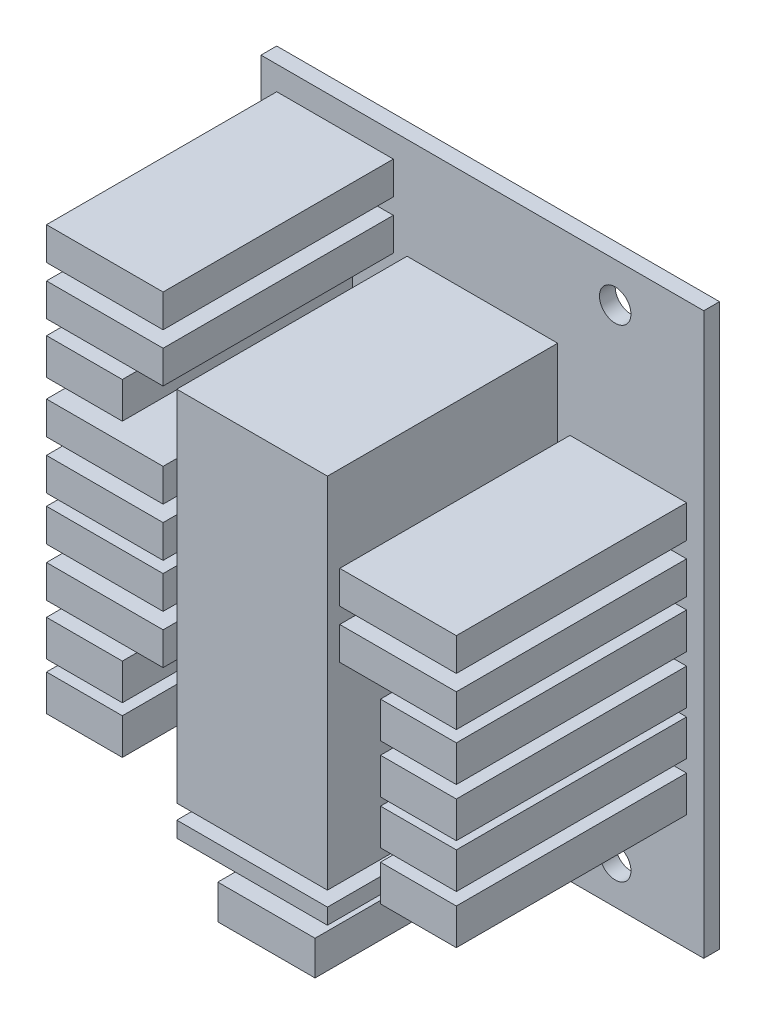
SolidWorks part; units mm, degrees
ref_plane "Plan de face" through (0, 0, 0) normal (0, 0, 1) x (1, 0, 0)
ref_plane "Plan de dessus" through (0, 0, 0) normal (0, 1, 0) x (1, 0, 0)
ref_plane "Plan de droite" through (0, 0, 0) normal (1, 0, 0) x (0, 0, -1)
sketch "Esquisse1" plane through (0, 0, 0) normal (0, 0, 1) x (1, 0, 0)
  line L0 (-22.5, -28.5) -> (22.5, -28.5)
  line L2 (22.5, -28.5) -> (22.5, 28.5)
  line L3 (22.5, 28.5) -> (-22.5, 28.5)
  line L4 (-22.5, -28.5) -> (-22.5, 28.5)
  line L5 (22.5, -28.5) -> (-22.5, 28.5) construction
  line L6 (22.5, 28.5) -> (-22.5, -28.5) construction
  circle A1 centre (13.5, 24.5) radius 1.6
  circle A2 centre (13.5, -24.5) radius 1.6
  circle A3 centre (-9.5, -24.5) radius 1.6
  point P0 (0, 0)
  dimension "D3" = 4
  dimension "D4" = 9
  dimension "D5" = 23
  dimension "D6" = 49
  dimension "D1" = 45
  dimension "D2" = 57
extrude "Boss.-Extru.1" add sketch "Esquisse1" along normal blind 1.6
sketch "Esquisse2" plane through (0, 0, 1.6) normal (0, 0, 1) x (1, 0, 0)
  line L0 (8.9033, 2.4603) -> (20.7535, 2.4603)
  line L1 (7.6551, -18.2198) -> (-7.6551, -18.2198)
  line L2 (7.6551, -18.2198) -> (7.6551, 18.2198)
  line L3 (7.6551, 18.2198) -> (-7.6551, 18.2198)
  line L4 (-7.6551, -18.2198) -> (-7.6551, 18.2198)
  line L5 (7.6551, -18.2198) -> (-7.6551, 18.2198) construction
  line L6 (7.6551, 18.2198) -> (-7.6551, -18.2198) construction
  line L7 (7.6551, -21.3078) -> (-7.6551, -21.3078)
  line L8 (7.6551, -21.3078) -> (7.6551, -19.71)
  line L9 (7.6551, -19.71) -> (-7.6551, -19.71)
  line L10 (-7.6551, -21.3078) -> (-7.6551, -19.71)
  line L11 (7.6551, -21.3078) -> (-7.6551, -19.71) construction
  line L12 (7.6551, -19.71) -> (-7.6551, -21.3078) construction
  line L13 (8.9033, 10.7312) -> (20.7535, 10.7312)
  line L14 (8.9033, 10.7312) -> (8.9033, 7.4015)
  line L15 (8.9033, 7.4015) -> (20.7535, 7.4015)
  line L16 (20.7535, 10.7312) -> (20.7535, 7.4015)
  line L17 (8.9033, 10.7312) -> (20.7535, 7.4015) construction
  line L18 (8.9033, 7.4015) -> (20.7535, 10.7312) construction
  line L20 (-3.4878, -26.5802) -> (6.3944, -26.5802)
  line L21 (-3.4878, -26.5802) -> (-3.4878, -23.0797)
  line L22 (-3.4878, -23.0797) -> (6.3944, -23.0797)
  line L23 (6.3944, -26.5802) -> (6.3944, -23.0797)
  line L24 (-3.4878, -26.5802) -> (6.3944, -23.0797) construction
  line L25 (20.7535, 5.7901) -> (20.7535, 2.4603)
  line L26 (8.9033, 5.7901) -> (20.7535, 2.4603) construction
  line L27 (8.9033, 5.7901) -> (20.7535, 5.7901)
  line L28 (8.9033, 5.7901) -> (8.9033, 2.4603)
  line L29 (8.9033, 2.4603) -> (20.7535, 5.7901) construction
  line L30 (13.0464, 1.2941) -> (13.0464, -2.3762)
  line L31 (13.0464, -2.3762) -> (20.7535, -2.3762)
  line L32 (20.7535, 1.2941) -> (20.7535, -2.3762)
  line L33 (13.0464, 1.2941) -> (20.7535, -2.3762) construction
  line L34 (13.0464, -2.3762) -> (20.7535, 1.2941) construction
  line L35 (13.0464, 1.2941) -> (20.7535, 1.2941)
  line L36 (13.0464, -3.6481) -> (13.0464, -7.3184)
  line L37 (13.0464, -7.3184) -> (20.7535, -7.3184)
  line L38 (20.7535, -3.6481) -> (20.7535, -7.3184)
  line L39 (13.0464, -3.6481) -> (20.7535, -7.3184) construction
  line L40 (13.0464, -7.3184) -> (20.7535, -3.6481) construction
  line L41 (13.0464, -3.6481) -> (20.7535, -3.6481)
  line L42 (13.0464, -8.1243) -> (13.0464, -11.7946)
  line L43 (13.0464, -11.7946) -> (20.7535, -11.7946)
  line L44 (20.7535, -8.1243) -> (20.7535, -11.7946)
  line L45 (13.0464, -8.1243) -> (20.7535, -11.7946) construction
  line L46 (13.0464, -11.7946) -> (20.7535, -8.1243) construction
  line L47 (13.0464, -8.1243) -> (20.7535, -8.1243)
  line L48 (13.0464, -13.0632) -> (13.0464, -16.7335)
  line L49 (13.0464, -16.7335) -> (20.7535, -16.7335)
  line L50 (20.7535, -13.0632) -> (20.7535, -16.7335)
  line L51 (13.0464, -13.0632) -> (20.7535, -16.7335) construction
  line L52 (13.0464, -16.7335) -> (20.7535, -13.0632) construction
  line L53 (13.0464, -13.0632) -> (20.7535, -13.0632)
  line L54 (-20.8965, 26.0764) -> (-20.8965, 22.7466)
  line L55 (-20.8965, 22.7466) -> (-9.0463, 22.7466)
  line L56 (-20.8965, 26.0764) -> (-9.0463, 22.7466) construction
  line L57 (-20.8965, 26.0764) -> (-9.0463, 26.0764)
  line L58 (-20.8965, 22.7466) -> (-9.0463, 26.0764) construction
  line L59 (-9.0463, 26.0764) -> (-9.0463, 22.7466)
  line L60 (-20.8965, 16.3024) -> (-13.1894, 12.632) construction
  line L61 (-20.8965, 16.3024) -> (-13.1894, 16.3024)
  line L62 (-20.8965, 12.632) -> (-13.1894, 12.632)
  line L63 (-13.1894, 16.3024) -> (-13.1894, 12.632)
  line L64 (-20.8965, 12.632) -> (-13.1894, 16.3024) construction
  line L65 (-20.8965, 16.3024) -> (-20.8965, 12.632)
  line L66 (-20.8965, 21.1264) -> (-9.0463, 21.1264)
  line L67 (-20.8965, 17.7967) -> (-9.0463, 21.1264) construction
  line L68 (-9.0463, 21.1264) -> (-9.0463, 17.7967)
  line L69 (-20.8965, 17.7967) -> (-9.0463, 17.7967)
  line L70 (-20.8965, 21.1264) -> (-9.0463, 17.7967) construction
  line L71 (-20.8965, 21.1264) -> (-20.8965, 17.7967)
  line L72 (-20.8965, 7.4015) -> (-9.0463, 10.7312) construction
  line L73 (-20.8965, 10.7312) -> (-9.0463, 10.7312)
  line L74 (-20.8965, 2.4515) -> (-9.0463, 5.7813) construction
  line L75 (-20.8965, 2.4515) -> (-9.0463, 2.4515)
  line L76 (-20.8965, 10.7312) -> (-9.0463, 7.4015) construction
  line L77 (-9.0463, 10.7312) -> (-9.0463, 7.4015)
  line L78 (-20.8965, 5.7813) -> (-20.8965, 2.4515)
  line L79 (-9.0463, 5.7813) -> (-9.0463, 2.4515)
  line L80 (-20.8965, 5.7813) -> (-9.0463, 2.4515) construction
  line L81 (-20.8965, 5.7813) -> (-9.0463, 5.7813)
  line L82 (-20.8965, 10.7312) -> (-20.8965, 7.4015)
  line L83 (-20.8965, 7.4015) -> (-9.0463, 7.4015)
  line L84 (-9.0463, 1.2941) -> (-9.0463, -2.0357)
  line L85 (-20.8965, -6.9856) -> (-9.0463, -6.9856)
  line L86 (-20.8965, -3.6558) -> (-9.0463, -3.6558)
  line L87 (-20.8965, -12.1502) -> (-13.1894, -8.4799) construction
  line L88 (-20.8965, 1.2941) -> (-9.0463, -2.0357) construction
  line L89 (-20.8965, -8.4799) -> (-20.8965, -12.1502)
  line L90 (-20.8965, -8.4799) -> (-13.1894, -8.4799)
  line L91 (-20.8965, -6.9856) -> (-9.0463, -3.6558) construction
  line L92 (-9.0463, -3.6558) -> (-9.0463, -6.9856)
  line L93 (-20.8965, -2.0357) -> (-9.0463, -2.0357)
  line L94 (-20.8965, -3.6558) -> (-20.8965, -6.9856)
  line L95 (-20.8965, 1.2941) -> (-20.8965, -2.0357)
  line L96 (-20.8965, -8.4799) -> (-13.1894, -12.1502) construction
  line L97 (-20.8965, 1.2941) -> (-9.0463, 1.2941)
  line L98 (-20.8965, -12.1502) -> (-13.1894, -12.1502)
  line L99 (-20.8965, -2.0357) -> (-9.0463, 1.2941) construction
  line L100 (-13.1894, -8.4799) -> (-13.1894, -12.1502)
  line L101 (-20.8965, -3.6558) -> (-9.0463, -6.9856) construction
  line L102 (-20.8965, -13.2915) -> (-13.1894, -13.2915)
  line L103 (-20.8965, -13.2915) -> (-13.1894, -16.9618) construction
  line L104 (-13.1894, -13.2915) -> (-13.1894, -16.9618)
  line L105 (-20.8965, -16.9618) -> (-13.1894, -13.2915) construction
  line L106 (-20.8965, -16.9618) -> (-13.1894, -16.9618)
  line L107 (-20.8965, -13.2915) -> (-20.8965, -16.9618)
  line L108 (-3.4878, -23.0797) -> (6.3944, -26.5802) construction
  point P0 (0, 0)
  point P6 (0, -20.5089)
  point P11 (14.8284, 9.0663)
  point P16 (1.4533, -24.8299)
  point P21 (14.8284, 4.1252)
  point P26 (16.8999, -0.541)
  point P31 (16.8999, -5.4833)
  point P36 (16.8999, -9.9595)
  point P41 (16.8999, -14.8984)
  point P46 (-14.9714, 24.4115)
  point P51 (-17.0429, 14.4672)
  point P56 (-14.9714, 19.4615)
  point P61 (-14.9714, 9.0663)
  point P66 (-14.9714, 4.1164)
  point P71 (-14.9714, -0.3708)
  point P76 (-17.0429, -10.3151)
  point P81 (-14.9714, -5.3207)
  point P86 (-17.0429, -15.1267)
extrude "Boss.-Extru.2" add sketch "Esquisse2" along normal blind 23.4
